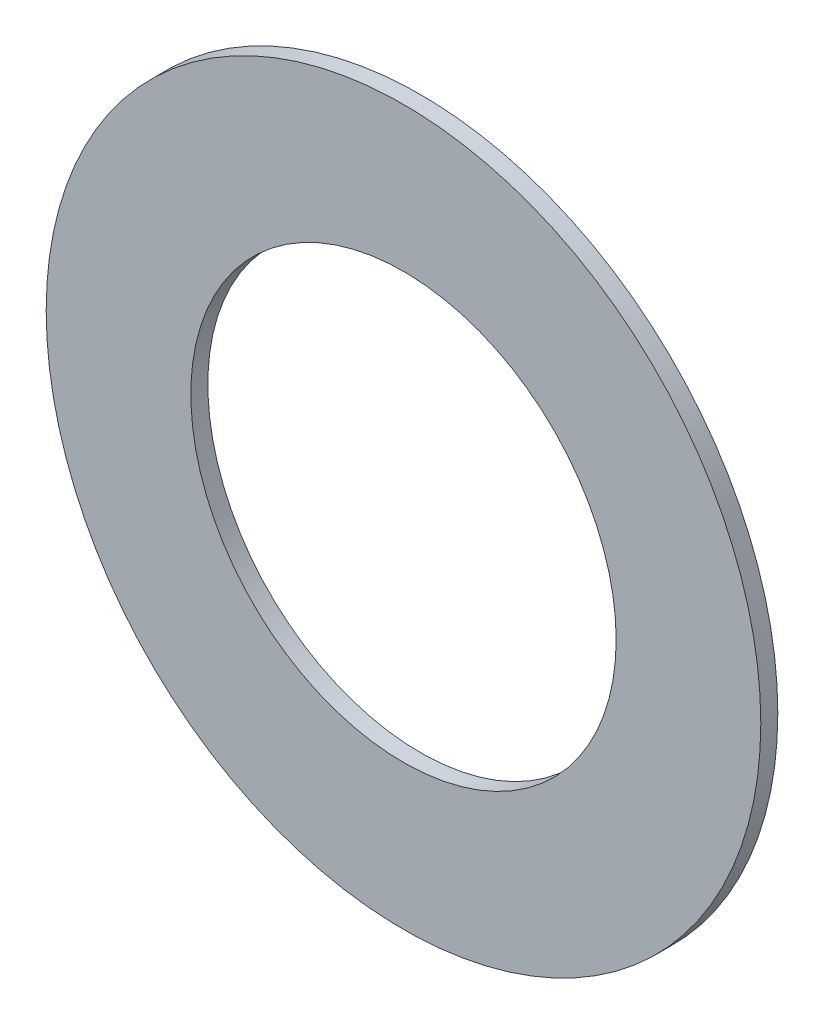
SolidWorks part; units mm, degrees
ref_plane "前视基准面" through (0, 0, 0) normal (0, 0, 1) x (1, 0, 0)
ref_plane "上视基准面" through (0, 0, 0) normal (0, 1, 0) x (1, 0, 0)
ref_plane "右视基准面" through (0, 0, 0) normal (1, 0, 0) x (0, 0, -1)
other "Configuration Table"
sketch "草图1" plane through (0, 0, 0) normal (0, 0, 1) x (1, 0, 0)
  circle A0 centre (0, 0) radius 21
  circle A1 centre (0, 0) radius 12.5
  dimension "D1" = 25
  dimension "D2" = 42
extrude "凸台-拉伸1" add sketch "草图1" along normal blind 1
